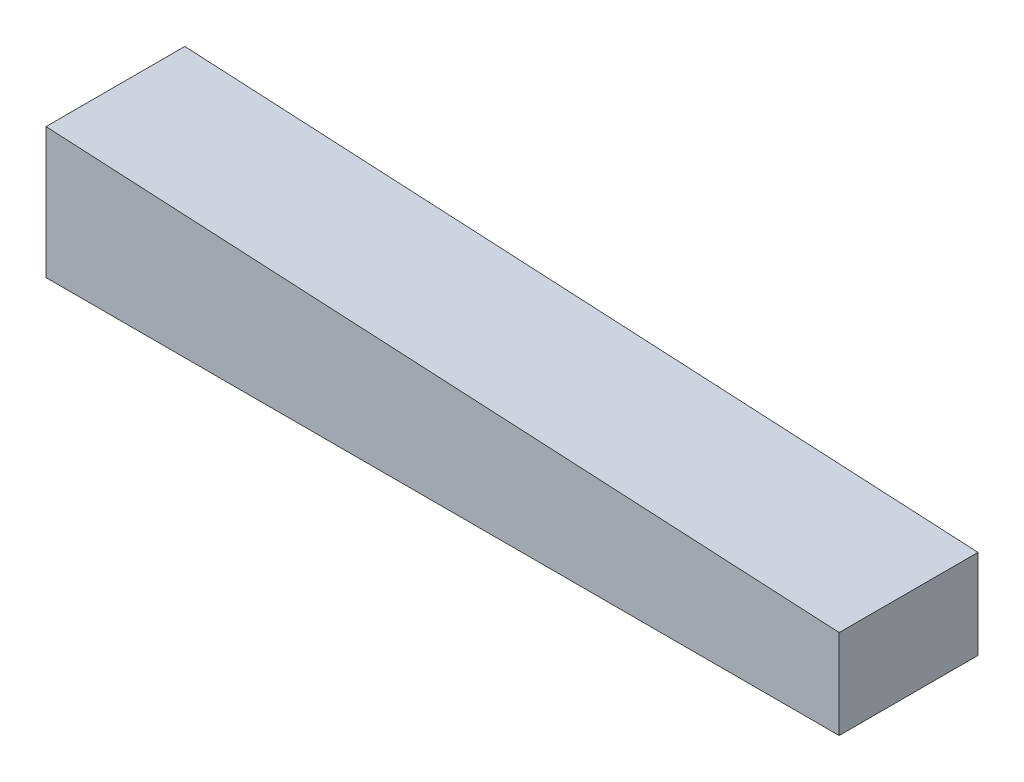
SolidWorks part; units mm, degrees
ref_plane "Front Plane" through (0, 0, 0) normal (0, 0, 1) x (1, 0, 0)
ref_plane "Top Plane" through (0, 0, 0) normal (0, 1, 0) x (1, 0, 0)
ref_plane "Right Plane" through (0, 0, 0) normal (1, 0, 0) x (0, 0, -1)
sketch "Sketch1" plane through (0, 0, 0) normal (0, 0, 1) x (1, 0, 0)
  line L0 (0, 48.4638) -> (0, -37.2713) construction
  line L1 (-33.9477, 0) -> (75.9965, 0) construction
  line L3 (0, 0) -> (80, 0)
  line L4 (0, 0) -> (0, 9)
  line L5 (0, 9) -> (80, 9)
  line L6 (80, 0) -> (80, 9)
extrude "Boss-Extrude1" add sketch "Sketch1" against normal blind 14 contours L4 L3 L6 L5
draft "Draft1" type of draft neutral plane draft angle 3 faces to draft 1 face at (40, 9, -7) neutral plane through (80, 0, -14) neutral plane normal (1, 0, 0) parameters "D1"=3
